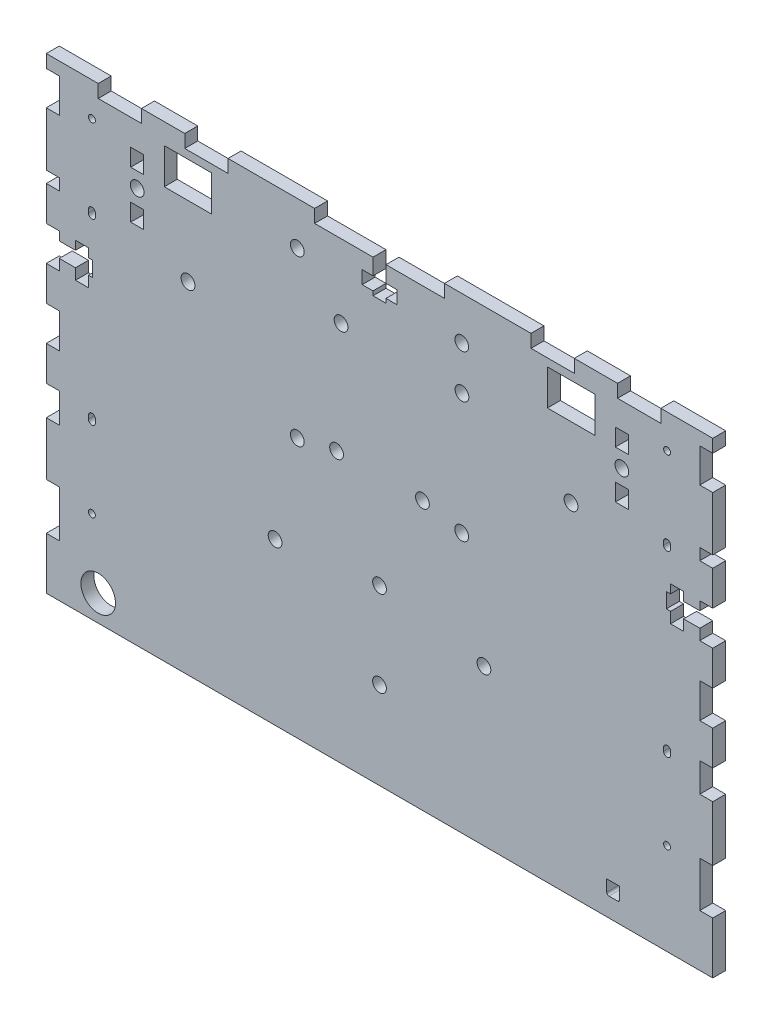
SolidWorks part; units mm, degrees
material "Balsa"
ref_plane "Alzado" through (0, 0, 0) normal (0, 0, 1) x (1, 0, 0)
ref_plane "Planta" through (0, 0, 0) normal (0, 1, 0) x (1, 0, 0)
ref_plane "Vista lateral" through (0, 0, 0) normal (1, 0, 0) x (0, 0, -1)
sketch "Croquis2" plane through (0, 0, 0) normal (0, 0, 1) x (1, 0, 0)
  line L0 (33590.334, 12954.4672) -> (33744.334, 12954.4672)
  line L1 (33593.334, 13059.4672) -> (33590.334, 13059.4672)
  line L2 (33744.334, 13059.4672) -> (33741.334, 13059.4672)
  line L3 (33609.834, 13038.4672) -> (33612.834, 13038.4672)
  line L4 (33612.834, 13038.4672) -> (33612.834, 13042.4672)
  line L5 (33612.834, 13042.4672) -> (33609.834, 13042.4672)
  line L6 (33609.834, 13042.4672) -> (33609.834, 13038.4672)
  line L7 (33609.834, 13049.4672) -> (33612.834, 13049.4672)
  line L8 (33612.834, 13049.4672) -> (33612.834, 13053.4672)
  line L9 (33612.834, 13053.4672) -> (33609.834, 13053.4672)
  line L10 (33609.834, 13053.4672) -> (33609.834, 13049.4672)
  line L11 (33721.834, 13053.4672) -> (33721.834, 13049.4672)
  line L12 (33721.834, 13049.4672) -> (33724.834, 13049.4672)
  line L13 (33724.834, 13049.4672) -> (33724.834, 13053.4672)
  line L14 (33724.834, 13053.4672) -> (33721.834, 13053.4672)
  line L15 (33724.834, 13038.4672) -> (33724.834, 13042.4672)
  line L16 (33724.834, 13042.4672) -> (33721.834, 13042.4672)
  line L17 (33721.834, 13042.4672) -> (33721.834, 13038.4672)
  line L18 (33721.834, 13038.4672) -> (33724.834, 13038.4672)
  line L19 (33617.5973, 13057.6704) -> (33617.5973, 13052.4265)
  line L20 (33628.5363, 13052.4265) -> (33628.5363, 13057.6704)
  line L21 (33717.0706, 13057.6704) -> (33717.0706, 13052.4265)
  line L22 (33706.1316, 13052.4265) -> (33706.1316, 13057.6704)
  line L23 (33741.334, 13022.9651) -> (33737.584, 13022.9651)
  line L24 (33741.334, 13020.4672) -> (33741.334, 13022.9651)
  line L25 (33744.334, 13020.4672) -> (33741.334, 13020.4672)
  line L26 (33744.334, 13012.4672) -> (33744.334, 13020.4672)
  line L27 (33744.334, 13012.4672) -> (33741.334, 13012.4672)
  line L28 (33741.334, 13012.4672) -> (33741.334, 13004.4672)
  line L29 (33744.334, 13004.4672) -> (33741.334, 13004.4672)
  line L30 (33744.334, 12996.4672) -> (33744.334, 13000.9189)
  line L31 (33744.334, 13001.2189) -> (33744.334, 13004.4672)
  line L32 (33744.334, 12996.4672) -> (33741.334, 12996.4672)
  line L33 (33744.334, 12954.4672) -> (33744.334, 12966.4681)
  line L34 (33590.334, 12966.4672) -> (33590.334, 12954.4672)
  line L35 (33590.334, 13004.4672) -> (33590.334, 12996.4672)
  line L36 (33590.334, 13028.4672) -> (33590.334, 13036.4672)
  line L37 (33590.334, 12966.4672) -> (33593.334, 12966.4672)
  line L38 (33593.334, 12996.4672) -> (33593.334, 12989.5947)
  line L39 (33593.334, 12977.2387) -> (33593.334, 12966.4672)
  line L40 (33590.334, 12996.4672) -> (33593.334, 12996.4672)
  line L41 (33632.334, 13059.4672) -> (33622.334, 13059.4672)
  line L42 (33665.834, 13059.4672) -> (33652.334, 13059.4672)
  line L43 (33590.334, 13004.4672) -> (33593.334, 13004.4672)
  line L44 (33593.334, 13012.4672) -> (33593.334, 13004.4672)
  line L45 (33590.334, 13012.4672) -> (33593.334, 13012.4672)
  line L46 (33590.334, 13012.4672) -> (33590.334, 13020.4672)
  line L47 (33590.334, 13020.4672) -> (33593.334, 13020.4672)
  line L48 (33593.334, 13020.4672) -> (33593.334, 13022.9651)
  line L49 (33593.334, 13022.9651) -> (33597.084, 13022.9651)
  line L50 (33597.084, 13020.4672) -> (33597.084, 13022.9651)
  line L51 (33597.084, 13020.4672) -> (33600.084, 13020.4672)
  line L52 (33600.084, 13020.4672) -> (33600.084, 13022.9651)
  line L53 (33600.084, 13022.9651) -> (33601.064, 13022.9651)
  line L54 (33601.064, 13022.9651) -> (33601.064, 13026.4593)
  line L55 (33600.084, 13026.4593) -> (33601.064, 13026.4593)
  line L56 (33600.084, 13026.4593) -> (33600.084, 13028.4672)
  line L57 (33597.084, 13028.4672) -> (33600.084, 13028.4672)
  line L58 (33597.084, 13026.4593) -> (33597.084, 13028.4672)
  line L59 (33593.334, 13026.4593) -> (33597.084, 13026.4593)
  line L60 (33593.334, 13026.4593) -> (33593.334, 13028.4672)
  line L61 (33590.334, 13028.4672) -> (33593.334, 13028.4672)
  line L62 (33682.334, 13059.4672) -> (33668.834, 13059.4672)
  line L63 (33712.334, 13059.4672) -> (33702.334, 13059.4672)
  line L64 (33590.334, 13036.4672) -> (33593.334, 13036.4672)
  line L65 (33593.334, 13036.4672) -> (33593.334, 13039.1279)
  line L66 (33593.334, 13051.6086) -> (33593.334, 13059.4672)
  line L67 (33590.334, 13059.4672) -> (33590.334, 13062.4672)
  line L68 (33744.334, 13059.4672) -> (33744.334, 13062.4672)
  line L69 (33741.334, 13026.4593) -> (33741.334, 13028.4672)
  line L70 (33741.334, 13036.4672) -> (33741.334, 13039.1275)
  line L71 (33741.334, 13051.6088) -> (33741.334, 13059.4672)
  line L72 (33741.334, 13026.4593) -> (33737.584, 13026.4593)
  line L73 (33737.584, 13026.4593) -> (33737.584, 13028.4672)
  line L74 (33737.584, 13028.4672) -> (33734.584, 13028.4672)
  line L75 (33734.584, 13026.4593) -> (33734.584, 13028.4672)
  line L76 (33734.584, 13026.4593) -> (33733.604, 13026.4593)
  line L77 (33733.604, 13022.9651) -> (33733.604, 13026.4593)
  line L78 (33734.584, 13022.9651) -> (33733.604, 13022.9651)
  line L79 (33734.584, 13020.4672) -> (33734.584, 13022.9651)
  line L80 (33737.584, 13020.4672) -> (33734.584, 13020.4672)
  line L81 (33737.584, 13020.4672) -> (33737.584, 13022.9651)
  line L82 (33722.834, 12959.3672) -> (33722.834, 12962.0672)
  line L83 (33719.834, 12962.0672) -> (33722.834, 12962.0672)
  line L84 (33719.834, 12959.3672) -> (33719.834, 12962.0672)
  line L85 (33720.334, 12958.8672) -> (33722.334, 12958.8672)
  line L86 (33617.5973, 13052.4265) -> (33617.5973, 13049.4265)
  line L87 (33617.5973, 13049.4265) -> (33628.5363, 13049.4265)
  line L88 (33628.5363, 13049.4265) -> (33628.5363, 13052.4265)
  line L89 (33617.5973, 13057.6704) -> (33628.5363, 13057.6704)
  line L90 (33706.1316, 13052.4265) -> (33706.1316, 13049.4265)
  line L91 (33706.1316, 13049.4265) -> (33717.0706, 13049.4265)
  line L92 (33717.0706, 13049.4265) -> (33717.0706, 13052.4265)
  line L93 (33706.1316, 13057.6704) -> (33717.0706, 13057.6704)
  line L94 (33741.334, 13028.4672) -> (33744.334, 13028.4672)
  line L95 (33744.334, 13028.4672) -> (33744.334, 13036.4672)
  line L96 (33741.334, 13036.4672) -> (33744.334, 13036.4672)
  line L97 (33600.086, 13036.2089) -> (33600.086, 13035.4089)
  line L98 (33601.686, 13035.4089) -> (33601.686, 13036.2089)
  line L99 (33732.9819, 13036.2089) -> (33732.9819, 13035.4089)
  line L100 (33734.5819, 13035.4089) -> (33734.5819, 13036.2089)
  line L101 (33600.086, 12994.9715) -> (33600.086, 12994.1715)
  line L102 (33601.686, 12994.1715) -> (33601.686, 12994.9715)
  line L103 (33732.9819, 12994.9715) -> (33732.9819, 12994.1715)
  line L104 (33734.5819, 12994.1715) -> (33734.5819, 12994.9715)
  line L105 (33590.334, 13062.4672) -> (33602.334, 13062.4672)
  line L106 (33602.334, 13062.4672) -> (33602.334, 13059.4672)
  line L107 (33612.334, 13059.4672) -> (33602.334, 13059.4672)
  line L108 (33612.334, 13062.4672) -> (33612.334, 13059.4672)
  line L109 (33612.334, 13062.4672) -> (33622.334, 13062.4672)
  line L110 (33622.334, 13062.4672) -> (33622.334, 13059.4672)
  line L113 (33652.334, 13062.4672) -> (33652.334, 13059.4672)
  line L116 (33682.334, 13062.4672) -> (33682.334, 13059.4672)
  line L117 (33665.834, 13059.4672) -> (33665.834, 13055.7172)
  line L118 (33665.834, 13055.7172) -> (33663.334, 13055.7172)
  line L119 (33663.334, 13055.7172) -> (33663.334, 13052.7172)
  line L120 (33665.834, 13052.7172) -> (33663.334, 13052.7172)
  line L121 (33665.834, 13052.7172) -> (33665.834, 13051.7372)
  line L122 (33668.834, 13051.7372) -> (33665.834, 13051.7372)
  line L123 (33668.834, 13052.7172) -> (33668.834, 13051.7372)
  line L124 (33671.334, 13052.7172) -> (33668.834, 13052.7172)
  line L125 (33671.334, 13055.7172) -> (33671.334, 13052.7172)
  line L126 (33671.334, 13055.7172) -> (33668.834, 13055.7172)
  line L127 (33668.834, 13059.4672) -> (33668.834, 13055.7172)
  line L130 (33712.334, 13062.4672) -> (33712.334, 13059.4672)
  line L131 (33712.334, 13062.4672) -> (33722.334, 13062.4672)
  line L132 (33722.334, 13062.4672) -> (33722.334, 13059.4672)
  line L133 (33722.334, 13059.4672) -> (33732.334, 13059.4672)
  line L134 (33732.334, 13062.4672) -> (33732.334, 13059.4672)
  line L135 (33732.334, 13062.4672) -> (33744.334, 13062.4672)
  line L136 (33632.334, 13059.4672) -> (33632.334, 13062.4672)
  line L137 (33632.334, 13062.4672) -> (33652.334, 13062.4672)
  line L140 (33702.334, 13062.4672) -> (33702.334, 13059.4672)
  line L141 (33702.334, 13062.4672) -> (33682.334, 13062.4672)
  line L142 (33744.334, 12966.4681) -> (33741.334, 12966.4681)
  line L143 (33741.334, 12966.4681) -> (33741.334, 12976.9443)
  line L144 (33741.334, 12989.7443) -> (33741.334, 12996.4672)
  line L146 (33590.334, 13039.1277) -> (33590.334, 13051.6086)
  line L147 (33590.334, 13051.6086) -> (33593.334, 13051.6086)
  line L148 (33590.334, 13039.1277) -> (33593.334, 13039.1279)
  line L149 (33590.334, 12977.2385) -> (33590.334, 12989.5945)
  line L150 (33590.334, 12977.2385) -> (33593.334, 12977.2387)
  line L151 (33590.334, 12989.5945) -> (33593.334, 12989.5947)
  line L152 (33744.334, 12976.9443) -> (33744.334, 12989.7443)
  line L153 (33744.334, 12989.7443) -> (33741.334, 12989.7443)
  line L154 (33744.334, 12976.9443) -> (33741.334, 12976.9443)
  line L155 (33744.334, 13051.6088) -> (33741.334, 13051.6088)
  line L156 (33744.334, 13039.1275) -> (33741.334, 13039.1275)
  line L157 (33744.334, 13039.1275) -> (33744.334, 13051.6088)
  line L163 (33744.334, 13000.9189) -> (33744.334, 13001.2189)
  arc A0 (33656.8568, 13042.473) -> (33658.3015, 13040.9222) centre (33658.444, 13042.5033) ccw
  arc A1 (33658.5522, 13040.9195) -> (33660.0311, 13042.4704) centre (33658.444, 13042.5033) ccw
  arc A2 (33660.0178, 13042.7112) -> (33658.5767, 13044.0852) centre (33658.444, 13042.5033) ccw
  arc A3 (33658.3146, 13044.0855) -> (33656.8698, 13042.7086) centre (33658.444, 13042.5033) ccw
  arc A4 (33684.7965, 13042.4977) -> (33686.1732, 13040.9299) centre (33686.384, 13042.5033) ccw
  arc A5 (33686.4265, 13040.9164) -> (33687.9714, 13042.485) centre (33686.384, 13042.5033) ccw
  arc A6 (33687.9544, 13042.7357) -> (33686.4103, 13044.0906) centre (33686.384, 13042.5033) ccw
  arc A7 (33686.1892, 13044.0788) -> (33684.8117, 13042.723) centre (33686.384, 13042.5033) ccw
  arc A8 (33689.8786, 12990.3509) -> (33691.3212, 12988.8522) centre (33691.464, 12990.4333) ccw
  arc A9 (33691.564, 12988.849) -> (33693.0492, 12990.3477) centre (33691.464, 12990.4333) ccw
  arc A10 (33693.0438, 12990.5894) -> (33691.5587, 12992.018) centre (33691.464, 12990.4333) ccw
  arc A11 (33691.3265, 12992.0148) -> (33689.8838, 12990.5862) centre (33691.464, 12990.4333) ccw
  arc A12 (33641.6223, 12991.5668) -> (33643.1539, 12990.1166) centre (33643.204, 12991.7033) ccw
  arc A13 (33643.3894, 12990.1267) -> (33644.7864, 12991.5769) centre (33643.204, 12991.7033) ccw
  arc A14 (33644.7882, 12991.8053) -> (33643.3912, 12993.2797) centre (33643.204, 12991.7033) ccw
  arc A15 (33643.152, 12993.29) -> (33641.6204, 12991.8155) centre (33643.204, 12991.7033) ccw
  circle A16 centre (33623.084, 13033.1672) radius 1.6
  circle A17 centre (33711.584, 13033.1672) radius 1.6
  circle A18 centre (33602.334, 12960.4672) radius 4
  arc A19 (33722.334, 12958.8672) -> (33722.834, 12959.3672) centre (33722.334, 12959.3672) ccw
  arc A20 (33719.834, 12959.3672) -> (33720.334, 12958.8672) centre (33720.334, 12959.3672) ccw
  arc A21 (33649.0741, 13053.9216) -> (33646.7527, 13052.3767) centre (33648.334, 13052.5172) ccw
  arc A22 (33649.4054, 13051.3458) -> (33649.3166, 13053.7641) centre (33648.334, 13052.5172) ccw
  arc A23 (33646.8056, 13052.0879) -> (33649.1735, 13051.1699) centre (33648.334, 13052.5172) ccw
  arc A24 (33687.0741, 13053.9216) -> (33684.7527, 13052.3767) centre (33686.334, 13052.5172) ccw
  arc A25 (33687.4054, 13051.3458) -> (33687.3166, 13053.7641) centre (33686.334, 13052.5172) ccw
  arc A26 (33684.8056, 13052.0879) -> (33687.1735, 13051.1699) centre (33686.334, 13052.5172) ccw
  arc A27 (33724.0741, 13047.3716) -> (33721.7527, 13045.8267) centre (33723.334, 13045.9672) ccw
  arc A28 (33724.4054, 13044.7958) -> (33724.3166, 13047.2141) centre (33723.334, 13045.9672) ccw
  arc A29 (33721.8056, 13045.5379) -> (33724.1735, 13044.6199) centre (33723.334, 13045.9672) ccw
  arc A30 (33668.0741, 12976.0466) -> (33665.7527, 12974.5017) centre (33667.334, 12974.6422) ccw
  arc A31 (33668.4054, 12973.4708) -> (33668.3166, 12975.8891) centre (33667.334, 12974.6422) ccw
  arc A32 (33665.8056, 12974.2129) -> (33668.1735, 12973.2949) centre (33667.334, 12974.6422) ccw
  arc A33 (33668.0741, 12995.8966) -> (33665.7527, 12994.3517) centre (33667.334, 12994.4922) ccw
  arc A34 (33668.4054, 12993.3208) -> (33668.3166, 12995.7391) centre (33667.334, 12994.4922) ccw
  arc A35 (33665.8056, 12994.0629) -> (33668.1735, 12993.1449) centre (33667.334, 12994.4922) ccw
  arc A36 (33643.9441, 12993.1077) -> (33641.6227, 12991.5628) centre (33643.204, 12991.7033) ccw
  arc A37 (33644.2754, 12990.5319) -> (33644.1866, 12992.9502) centre (33643.204, 12991.7033) ccw
  arc A38 (33641.6756, 12991.274) -> (33644.0435, 12990.356) centre (33643.204, 12991.7033) ccw
  arc A39 (33612.0741, 13047.3716) -> (33609.7527, 13045.8267) centre (33611.334, 13045.9672) ccw
  arc A40 (33612.4054, 13044.7958) -> (33612.3166, 13047.2141) centre (33611.334, 13045.9672) ccw
  arc A41 (33609.8056, 13045.5379) -> (33612.1735, 13044.6199) centre (33611.334, 13045.9672) ccw
  arc A42 (33649.0741, 13015.9216) -> (33646.7527, 13014.3767) centre (33648.334, 13014.5172) ccw
  arc A43 (33649.4054, 13013.3458) -> (33649.3166, 13015.7641) centre (33648.334, 13014.5172) ccw
  arc A44 (33646.8056, 13014.0879) -> (33649.1735, 13013.1699) centre (33648.334, 13014.5172) ccw
  arc A45 (33658.1491, 13017.8716) -> (33655.8277, 13016.3267) centre (33657.409, 13016.4672) ccw
  arc A46 (33658.4804, 13015.2958) -> (33658.3916, 13017.7141) centre (33657.409, 13016.4672) ccw
  arc A47 (33655.8806, 13016.0379) -> (33658.2485, 13015.1199) centre (33657.409, 13016.4672) ccw
  arc A48 (33677.9991, 13017.8716) -> (33675.6777, 13016.3267) centre (33677.259, 13016.4672) ccw
  arc A49 (33678.3304, 13015.2958) -> (33678.2416, 13017.7141) centre (33677.259, 13016.4672) ccw
  arc A50 (33675.7306, 13016.0379) -> (33678.0985, 13015.1199) centre (33677.259, 13016.4672) ccw
  arc A51 (33687.0741, 13015.9216) -> (33684.7527, 13014.3767) centre (33686.334, 13014.5172) ccw
  arc A52 (33687.4054, 13013.3458) -> (33687.3166, 13015.7641) centre (33686.334, 13014.5172) ccw
  arc A53 (33684.8056, 13014.0879) -> (33687.1735, 13013.1699) centre (33686.334, 13014.5172) ccw
  arc A54 (33601.2083, 13055.4159) -> (33600.088, 13054.6279) centre (33600.886, 13054.6837) ccw
  arc A55 (33601.526, 13054.2037) -> (33601.4482, 13055.2528) centre (33600.886, 13054.6837) ccw
  arc A56 (33600.1602, 13054.3471) -> (33601.2557, 13053.9742) centre (33600.886, 13054.6837) ccw
  arc A57 (33600.086, 12994.1715) -> (33600.088, 12994.1157) centre (33600.886, 12994.1715) ccw
  arc A58 (33601.526, 12993.6915) -> (33601.686, 12994.1715) centre (33600.886, 12994.1715) ccw
  arc A59 (33600.1602, 12993.8349) -> (33601.2557, 12993.462) centre (33600.886, 12994.1715) ccw
  arc A60 (33601.2083, 12976.4031) -> (33600.088, 12975.6151) centre (33600.886, 12975.671) ccw
  arc A61 (33601.526, 12975.191) -> (33601.4482, 12976.2401) centre (33600.886, 12975.671) ccw
  arc A62 (33600.1602, 12975.3344) -> (33601.2557, 12974.9615) centre (33600.886, 12975.671) ccw
  arc A63 (33734.1043, 13055.4159) -> (33732.9839, 13054.6279) centre (33733.7819, 13054.6837) ccw
  arc A64 (33734.4219, 13054.2037) -> (33734.3441, 13055.2528) centre (33733.7819, 13054.6837) ccw
  arc A65 (33733.0562, 13054.3471) -> (33734.1516, 13053.9742) centre (33733.7819, 13054.6837) ccw
  arc A66 (33734.1043, 13036.9411) -> (33732.9819, 13036.2089) centre (33733.7819, 13036.2089) ccw
  arc A67 (33734.5819, 13036.2089) -> (33734.3441, 13036.778) centre (33733.7819, 13036.2089) ccw
  arc A68 (33732.9819, 12994.1715) -> (33732.9839, 12994.1157) centre (33733.7819, 12994.1715) ccw
  arc A69 (33734.4219, 12993.6915) -> (33734.5819, 12994.1715) centre (33733.7819, 12994.1715) ccw
  arc A70 (33733.0562, 12993.8349) -> (33734.1516, 12993.462) centre (33733.7819, 12994.1715) ccw
  arc A71 (33734.1043, 12976.4031) -> (33732.9839, 12975.6151) centre (33733.7819, 12975.671) ccw
  arc A72 (33734.4219, 12975.191) -> (33734.3441, 12976.2401) centre (33733.7819, 12975.671) ccw
  arc A73 (33733.0562, 12975.3344) -> (33734.1516, 12974.9615) centre (33733.7819, 12975.671) ccw
  arc A74 (33601.526, 13034.9289) -> (33601.686, 13035.4089) centre (33600.886, 13035.4089) ccw
  arc A75 (33600.1602, 13035.0723) -> (33601.2557, 13034.6994) centre (33600.886, 13035.4089) ccw
  arc A76 (33601.686, 13036.2089) -> (33600.086, 13036.2089) centre (33600.886, 13036.2089) ccw
  arc A77 (33732.9819, 13035.4089) -> (33732.9839, 13035.3531) centre (33733.7819, 13035.4089) ccw
  arc A78 (33734.4219, 13034.9289) -> (33734.5819, 13035.4089) centre (33733.7819, 13035.4089) ccw
  arc A79 (33733.0562, 13035.0723) -> (33734.1516, 13034.6994) centre (33733.7819, 13035.4089) ccw
  arc A80 (33600.1602, 12993.8349) -> (33601.2557, 12993.462) centre (33600.886, 12994.1715) ccw
  arc A81 (33601.686, 12994.9715) -> (33600.086, 12994.9715) centre (33600.886, 12994.9715) ccw
  arc A82 (33733.0562, 12993.8349) -> (33734.1516, 12993.462) centre (33733.7819, 12994.1715) ccw
  arc A83 (33734.5819, 12994.9715) -> (33732.9819, 12994.9715) centre (33733.7819, 12994.9715) ccw
  circle A84 centre (33600.886, 13054.6837) radius 0.8
  circle A85 centre (33611.334, 13045.9672) radius 1.5875
  arc A86 (33600.086, 13035.4089) -> (33601.686, 13035.4089) centre (33600.886, 13035.4089) ccw
  circle A87 centre (33600.886, 12975.671) radius 0.8
  arc A88 (33600.086, 12994.1715) -> (33601.686, 12994.1715) centre (33600.886, 12994.1715) ccw
  circle A89 centre (33648.334, 13052.5172) radius 1.5875
  circle A90 centre (33658.444, 13042.5033) radius 1.5875
  circle A91 centre (33657.409, 13016.4672) radius 1.5875
  circle A92 centre (33648.334, 13014.5172) radius 1.5875
  circle A93 centre (33667.334, 12974.6422) radius 1.5875
  circle A94 centre (33667.334, 12994.4922) radius 1.5875
  circle A95 centre (33691.464, 12990.4333) radius 1.5875
  circle A96 centre (33686.334, 13014.5172) radius 1.5875
  circle A97 centre (33677.259, 13016.4672) radius 1.5875
  circle A98 centre (33686.384, 13042.5033) radius 1.5875
  circle A99 centre (33686.334, 13052.5172) radius 1.5875
  circle A100 centre (33733.7819, 13054.6837) radius 0.8
  circle A101 centre (33723.334, 13045.9672) radius 1.5875
  arc A102 (33734.5819, 13036.2089) -> (33732.9819, 13036.2089) centre (33733.7819, 13036.2089) ccw
  arc A103 (33732.9819, 13035.4089) -> (33734.5819, 13035.4089) centre (33733.7819, 13035.4089) ccw
  circle A104 centre (33733.7819, 12975.671) radius 0.8
  arc A105 (33732.9819, 12994.1715) -> (33734.5819, 12994.1715) centre (33733.7819, 12994.1715) ccw
extrude "Saliente-Extruir1" add sketch "Croquis2" along normal blind 3 contours L30 L163 L31 L29 L28 L27 L26 L25 L24 L23 L81 L80 L79 L78 L77 L76 L75 L74 L73 L72 L69 L94 L95 L96 L70 L156 L157 L155 L71 L2 L68 L135 L134 L133 L132 L131 L130 L63 L140 L141 L116 L62 L127 L126 L125 L124 L123 L122 L121 L120 L119
